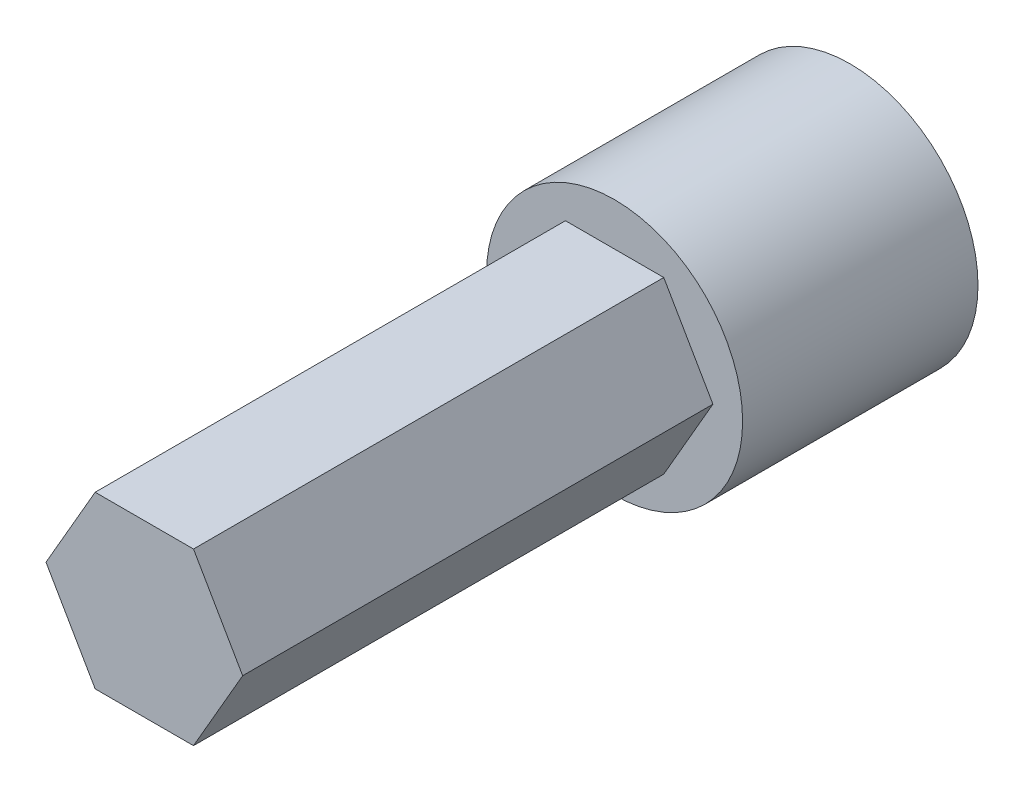
SolidWorks part; units mm, degrees
ref_plane "Front Plane" through (0, 0, 0) normal (0, 0, 1) x (1, 0, 0)
ref_plane "Top Plane" through (0, 0, 0) normal (0, 1, 0) x (1, 0, 0)
ref_plane "Right Plane" through (0, 0, 0) normal (1, 0, 0) x (0, 0, -1)
sketch "Sketch1" plane through (0, 0, 0) normal (0, 0, 1) x (1, 0, 0)
  line L1 (2.3024, 3.9878) -> (-2.3024, 3.9878)
  line L2 (-2.3024, 3.9878) -> (-4.6047, 0)
  line L3 (-4.6047, 0) -> (-2.3024, -3.9878)
  line L4 (-2.3024, -3.9878) -> (2.3024, -3.9878)
  line L5 (2.3024, -3.9878) -> (4.6047, 0)
  line L6 (4.6047, 0) -> (2.3024, 3.9878)
  circle A0 centre (0, 0) radius 3.9878 construction
  dimension "D1" = 7.9756
extrude "Boss-Extrude1" add sketch "Sketch1" against normal blind 22.0218
sketch "Sketch3" plane through (0, 0, -22.0218) normal (0, 0, -1) x (-1, 0, 0)
  circle A0 centre (0, 0) radius 5.9944
  dimension "D1" = 11.9888
extrude "Boss-Extrude2" add sketch "Sketch3" along normal blind 11.0236
sketch "Sketch4" plane through (0, 0, -33.0454) normal (0, 0, -1) x (-1, 0, 0)
  circle A0 centre (0, 0) radius 3.0226
  dimension "D1" = 6.0452
extrude "Cut-Extrude1" cut sketch "Sketch4" against normal blind 12.5476
ref_plane "Plane1" through (-5.1913, -2.9972, 0) normal (-0.866, -0.5, 0) x (0, 0, 1)
sketch "Sketch5" plane through (-5.1913, -2.9972, 0) normal (-0.866, -0.5, 0) x (0, 0, 1)
  line L0 (-33.0454, 5.9944) -> (-33.0454, -5.9944) construction
  circle A0 centre (-29.2354, 0) radius 1.27
  dimension "D1" = 2.54
  dimension "D2" = 3.81
extrude "Cut-Extrude2" cut sketch "Sketch5" against normal blind 6.35 contours A0
